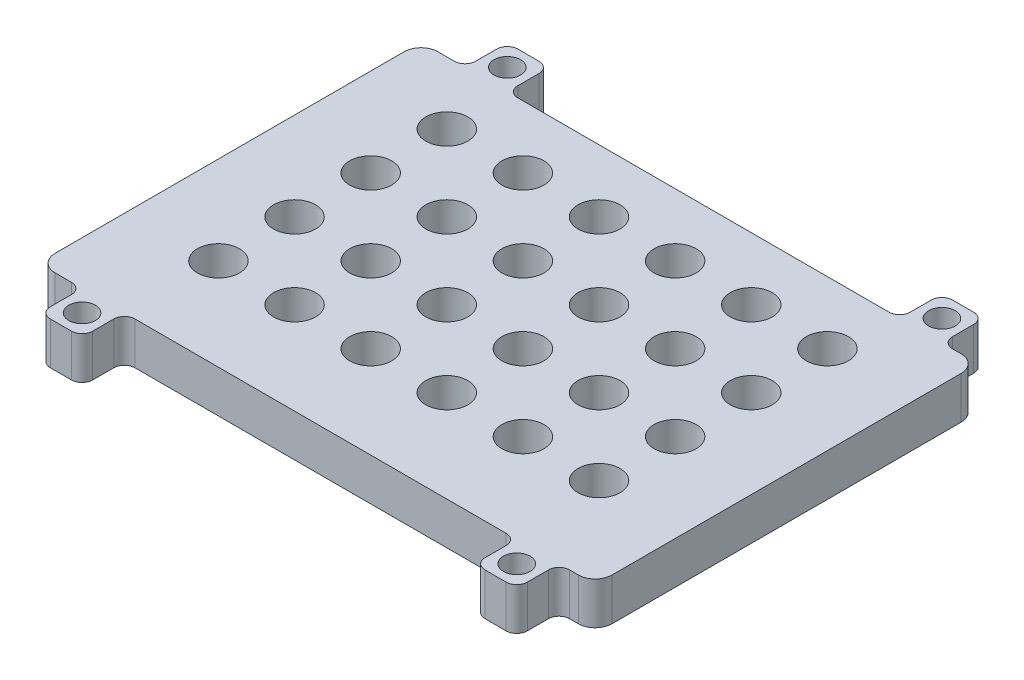
SolidWorks part; units mm, degrees
ref_plane "Front Plane" through (0, 0, 0) normal (0, 0, 1) x (1, 0, 0)
ref_plane "Top Plane" through (0, 0, 0) normal (0, 1, 0) x (1, 0, 0)
ref_plane "Right Plane" through (0, 0, 0) normal (1, 0, 0) x (0, 0, -1)
sketch "Sketch1" plane through (0, 0, 0) normal (0, 1, 0) x (1, 0, 0)
  line L0 (-45, 30.5) -> (-65.8635, 30.5) construction
  line L1 (65.8635, 45.2755) -> (-65.8635, 45.2755)
  line L2 (65.8635, 45.2755) -> (65.8635, -45.2755)
  line L3 (65.8635, -45.2755) -> (-65.8635, -45.2755)
  line L4 (-65.8635, 45.2755) -> (-65.8635, -45.2755)
  line L5 (65.8635, 45.2755) -> (-65.8635, -45.2755) construction
  line L6 (65.8635, -45.2755) -> (-65.8635, 45.2755) construction
  line L8 (45, -23.5) -> (65.8635, -23.5) construction
  line L9 (45, -23.5) -> (45, -45.2755) construction
  circle A0 centre (-45, 30.5) radius 3.5
  circle A1 centre (-27, 30.5) radius 3.5
  circle A2 centre (-9, 30.5) radius 3.5
  circle A3 centre (9, 30.5) radius 3.5
  circle A4 centre (27, 30.5) radius 3.5
  circle A5 centre (45, 30.5) radius 3.5
  circle A6 centre (-27, 12.5) radius 3.5
  circle A7 centre (-9, 12.5) radius 3.5
  circle A8 centre (9, 12.5) radius 3.5
  circle A9 centre (27, 12.5) radius 3.5
  circle A10 centre (45, 12.5) radius 3.5
  circle A11 centre (-27, -5.5) radius 3.5
  circle A12 centre (-9, -5.5) radius 3.5
  circle A13 centre (9, -5.5) radius 3.5
  circle A14 centre (27, -5.5) radius 3.5
  circle A15 centre (45, -5.5) radius 3.5
  circle A16 centre (-27, -23.5) radius 3.5
  circle A17 centre (-9, -23.5) radius 3.5
  circle A18 centre (9, -23.5) radius 3.5
  circle A19 centre (27, -23.5) radius 3.5
  circle A20 centre (45, -23.5) radius 3.5
  circle A21 centre (-45, 12.5) radius 3.5
  circle A22 centre (-45, -5.5) radius 3.5
  circle A23 centre (-45, -23.5) radius 3.5
  point P0 (0, 0)
  dimension "D3" = 7
  dimension "D4" = 6
  dimension "D1" = 131.727
  dimension "D2" = 90.551
  dimension "D6" = 18
  dimension "D7" = 18
  dimension "D8" = 21.7755
  dimension "D5" = 4
extrude "Boss-Extrude1" add sketch "Sketch1" along normal blind 10
sketch "Sketch3" plane through (0, 0, 0) normal (0, -1, 0) x (1, 0, 0)
  line L0 (65.8635, -45.2755) -> (-65.8635, -45.2755) construction
  line L1 (47.3134, -45.2755) -> (57.3134, -45.2755)
  line L2 (47.3134, -45.2755) -> (47.3134, -55.2755)
  line L3 (47.3134, -55.2755) -> (57.3134, -55.2755)
  line L4 (57.3134, -45.2755) -> (57.3134, -55.2755)
  line L5 (-65.8635, 45.2755) -> (65.8635, 45.2755) construction
  line L6 (-45.4727, -45.2755) -> (-55.4727, -45.2755)
  line L7 (-45.4727, -45.2755) -> (-45.4727, -55.2755)
  line L8 (-45.4727, -55.2755) -> (-55.4727, -55.2755)
  line L9 (-55.4727, -45.2755) -> (-55.4727, -55.2755)
  line L10 (-55.4727, 45.2755) -> (-45.4727, 45.2755)
  line L11 (-55.4727, 45.2755) -> (-55.4727, 55.2755)
  line L12 (-55.4727, 55.2755) -> (-45.4727, 55.2755)
  line L13 (-45.4727, 45.2755) -> (-45.4727, 55.2755)
  line L14 (-55.4727, -45.2755) -> (-65.8635, -45.2755) construction
  line L15 (47.3134, 45.2755) -> (57.3134, 45.2755)
  line L16 (47.3134, 45.2755) -> (47.3134, 55.2755)
  line L17 (47.3134, 55.2755) -> (57.3134, 55.2755)
  line L18 (57.3134, 45.2755) -> (57.3134, 55.2755)
  line L19 (-45.4727, 45.2755) -> (-55.4727, 55.2755) construction
  line L20 (-45.4727, -45.2755) -> (-55.4727, -55.2755) construction
  line L21 (-55.4727, 45.2755) -> (-65.8635, 45.2755) construction
  line L22 (47.3134, 55.2755) -> (57.3134, 45.2755) construction
  line L23 (47.3134, -55.2755) -> (57.3134, -45.2755) construction
  point P20 (-50.4727, 50.2755)
  point P23 (-50.4727, -50.2755)
  point P24 (45, 23.5)
  point P29 (52.3134, 50.2755)
  point P31 (52.3134, -50.2755)
  dimension "D1" = 10
  dimension "D2" = 102.7861
  dimension "D3" = 102.7861
  dimension "D4" = 7.3134
  dimension "D5" = 7.3134
  dimension "D6" = 13.5501
  dimension "D7" = 15.3908
  dimension "D8" = 13.5501
  dimension "D9" = 15.3908
extrude "Boss-Extrude3" add sketch "Sketch3" against normal up to surface (10 mm away) up to face at (-45, 10, 9)
sketch "Sketch4" plane through (0, 0, 0) normal (0, -1, 0) x (-1, 0, 0)
  line L0 (-57.3134, 55.2755) -> (-47.3134, 45.2755) construction
  line L1 (55.4727, 55.2755) -> (45.4727, 45.2755) construction
  line L2 (-57.3134, -45.2755) -> (-47.3134, -55.2755) construction
  line L3 (55.4727, -45.2755) -> (45.4727, -55.2755) construction
  circle A0 centre (-52.3134, -50.2755) radius 3.15
  circle A1 centre (50.4727, -50.2755) radius 3.15
  circle A2 centre (50.4727, 50.2755) radius 3.15
  circle A3 centre (-52.3134, 50.2755) radius 3.15
  dimension "D1" = 6.3
extrude "Cut-Extrude2" cut sketch "Sketch4" against normal through all
fillet "Fillet2" radius 2.5 16 edges at (47.3134, 5, 55.2755) (47.3134, 5, 45.2755) (57.3134, 5, 55.2755) (57.3134, 5, 45.2755) (-45.4727, 5, 55.2755) (-55.4727, 5, 55.2755) (-45.4727, 5, -45.2755) (-45.4727, 5, -55.2755) (-55.4727, 5, -45.2755) (-55.4727, 5, -55.2755) (47.3134, 5, -55.2755) (57.3134, 5, -55.2755)
fillet "Fillet3" radius 4 4 edges at (-65.8635, 5, -45.2755) (-65.8635, 5, 45.2755) (65.8635, 5, 45.2755) (65.8635, 5, -45.2755)
sketch "Sketch5" plane through (0, 10, 0) normal (0, 1, 0) x (1, 0, 0)
  circle A0 centre (45, -23.5) radius 4.975
  circle A1 centre (27, -23.5) radius 4.975
  circle A2 centre (9, -23.5) radius 4.975
  circle A3 centre (-9, -23.5) radius 4.975
  circle A4 centre (-27, -23.5) radius 4.975
  circle A5 centre (-45, -23.5) radius 4.975
  circle A6 centre (45, -5.5) radius 4.975
  circle A7 centre (27, -5.5) radius 4.975
  circle A8 centre (9, -5.5) radius 4.975
  circle A9 centre (-9, -5.5) radius 4.975
  circle A10 centre (-27, -5.5) radius 4.975
  circle A11 centre (-45, -5.5) radius 4.975
  circle A12 centre (45, 12.5) radius 4.975
  circle A13 centre (27, 12.5) radius 4.975
  circle A14 centre (9, 12.5) radius 4.975
  circle A15 centre (-9, 12.5) radius 4.975
  circle A16 centre (-27, 12.5) radius 4.975
  circle A17 centre (-45, 12.5) radius 4.975
  circle A18 centre (45, 30.5) radius 4.975
  circle A19 centre (27, 30.5) radius 4.975
  circle A20 centre (9, 30.5) radius 4.975
  circle A21 centre (-9, 30.5) radius 4.975
  circle A22 centre (-27, 30.5) radius 4.975
  circle A23 centre (-45, 30.5) radius 4.975
  dimension "D1" = 9.95
extrude "Cut-Extrude3" cut sketch "Sketch5" against normal blind 9.5
